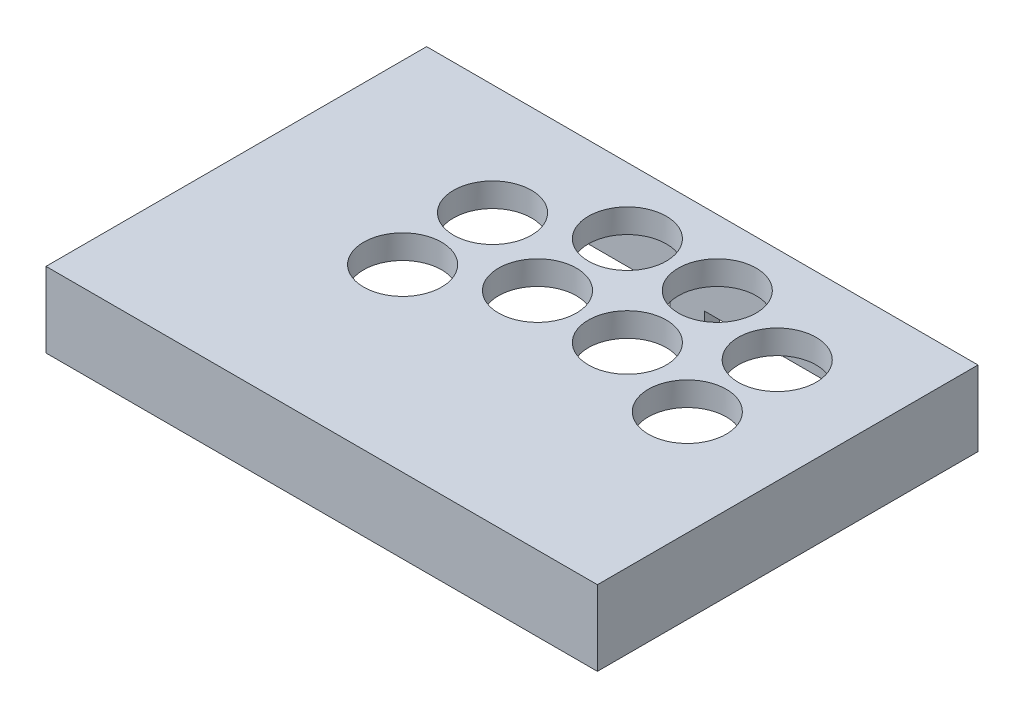
SolidWorks part; units mm, degrees
ref_plane "Front Plane" through (0, 0, 0) normal (0, 0, 1) x (1, 0, 0)
ref_plane "Top Plane" through (0, 0, 0) normal (0, 1, 0) x (1, 0, 0)
ref_plane "Right Plane" through (0, 0, 0) normal (1, 0, 0) x (0, 0, -1)
sketch "Sketch1" plane through (0, 0, 0) normal (0, 1, 0) x (1, 0, 0)
  line L0 (-58.3649, 63.5) -> (-58.3649, -63.5) construction
  line L5 (127, 63.5) -> (-127, 63.5)
  line L6 (127, 63.5) -> (127, -63.5)
  line L7 (127, -63.5) -> (-127, -63.5)
  line L8 (-127, 63.5) -> (-127, -63.5)
  point P0 (0, 0)
  dimension "D1" = 254
  dimension "D2" = 68.6351
  dimension "1" = 127
extrude "Boss-Extrude2" add sketch "Sketch1" along normal blind 19.05
sketch "Sketch2" plane through (0, 0, 0) normal (0, -1, 0) x (1, 0, 0)
  line L12 (-122, 58.5) -> (-122, -58.5)
  line L13 (-122, -58.5) -> (122, -58.5)
  line L14 (122, -58.5) -> (122, 58.5)
  line L15 (122, 58.5) -> (-122, 58.5)
  line L16 (-122, 58.5) -> (-122, -58.5)
  line L17 (-122, -58.5) -> (122, -58.5)
  line L18 (122, -58.5) -> (122, 58.5)
  line L19 (122, 58.5) -> (-122, 58.5)
  dimension "D1" = 5
extrude "Cut-Extrude1" cut sketch "Sketch2" against normal blind 17.05 contours L16 L17 L18 L19
sketch "Sketch4" plane through (0, 19.05, 0) normal (0, 1, 0) x (1, 0, 0)
  line L0 (-57, 63.5) -> (-57, -63.5) construction
  line L1 (127, 63.5) -> (-127, 63.5) construction
  line L2 (-127, -63.5) -> (127, -63.5) construction
  line L3 (127, -63.5) -> (127, 63.5) construction
  circle A0 centre (92, 1.5) radius 13
  circle A1 centre (92, 31.5) radius 13
  circle A2 centre (62, 11.5) radius 13
  circle A3 centre (62, 41.5) radius 13
  circle A6 centre (32, 11.5) radius 13
  circle A7 centre (32, 41.5) radius 13
  circle A8 centre (2, -3.5) radius 13
  circle A9 centre (2, 26.5) radius 13
  dimension "D2" = 26
  dimension "D3" = 65
  dimension "D5" = 35
  dimension "D6" = 19
  dimension "D7" = 26
  dimension "D12" = 26
  dimension "D13" = 26
  dimension "D14" = 30
  dimension "D17" = 26
  dimension "D18" = 26
  dimension "D1" = 70
  dimension "D4" = 35
  dimension "D8" = 75
  dimension "D9" = 30
  dimension "D10" = 30
  dimension "D11" = 30
  dimension "D15" = 30
  dimension "D16" = 30
  dimension "D19" = 60
  dimension "D20" = 30
  dimension "D21" = 30
  dimension "D22" = 30
extrude "Cut-Extrude2" cut sketch "Sketch4" against normal blind 17.05 contours A1 | A0 | A7 | A3 | A2 | A6 | A8 | A9
sketch "Sketch5" plane through (0, 0, 0) normal (0, -1, 0) x (1, 0, 0)
  line L0 (-57, 63.5) -> (-57, -63.5) construction
  line L1 (-127, 63.5) -> (127, 63.5) construction
  line L2 (127, -63.5) -> (-127, -63.5) construction
  line L3 (-57, 63.5) -> (-57, -63.5)
  line L4 (-57, -63.5) -> (-127, -63.5)
  line L5 (-127, -63.5) -> (-127, 63.5)
  line L6 (-127, 63.5) -> (-57, 63.5)
  dimension "D1" = 70
extrude "Cut-Extrude3" cut sketch "Sketch5" against normal blind 45
sketch "Sketch6" plane through (0, 17.05, 0) normal (0, -1, 0) x (1, 0, 0)
  line L0 (-57, 58.5) -> (-57, -58.5)
  line L1 (-57, -58.5) -> (-52, -58.5)
  line L2 (-57, -58.5) -> (122, -58.5) construction
  line L3 (-52, -58.5) -> (-52, 58.5)
  line L4 (122, 58.5) -> (-57, 58.5) construction
  line L5 (-52, 58.5) -> (-57, 58.5)
  dimension "D1" = 5
extrude "Boss-Extrude3" add sketch "Sketch6" along normal up to vertex (17.05 mm away)
sketch "Sketch7" plane through (0, 19.05, 0) normal (0, 1, 0) x (1, 0, 0)
  line L4 (127, 63.5) -> (-57, 63.5)
  line L5 (-57, 63.5) -> (-57, -63.5)
  line L6 (-57, -63.5) -> (127, -63.5)
  line L7 (127, -63.5) -> (127, 63.5)
  line L8 (127, 63.5) -> (-57, 63.5)
  line L9 (-57, 63.5) -> (-57, -63.5)
  line L10 (-57, -63.5) -> (127, -63.5)
  line L11 (127, -63.5) -> (127, 63.5)
  circle A1 centre (2, 26.5) radius 13
  circle A2 centre (2, 26.5) radius 13
  circle A3 centre (2, -3.5) radius 13
  circle A4 centre (2, -3.5) radius 13
  circle A5 centre (32, 11.5) radius 13
  circle A6 centre (32, 11.5) radius 13
  circle A7 centre (92, 31.5) radius 13
  circle A8 centre (92, 31.5) radius 13
  circle A9 centre (62, 11.5) radius 13
  circle A10 centre (62, 11.5) radius 13
  circle A11 centre (62, 41.5) radius 13
  circle A12 centre (62, 41.5) radius 13
  circle A13 centre (32, 41.5) radius 13
  circle A14 centre (32, 41.5) radius 13
  circle A15 centre (92, 1.5) radius 13
  circle A16 centre (92, 1.5) radius 13
  dimension "D1" = 0
  dimension "D2" = 0
  dimension "D3" = 0
  dimension "D4" = 0
  dimension "D5" = 0
  dimension "D6" = 0
  dimension "D7" = 0
  dimension "D8" = 0
  dimension "D9" = 0
extrude "Boss-Extrude4" add sketch "Sketch7" along normal blind 6
sketch "Sketch8" plane through (0, 17.05, 0) normal (0, -1, 0) x (1, 0, 0)
  line L0 (118.5, 58.5) -> (122, 58.5)
  line L1 (122, 58.5) -> (122, 55)
  line L4 (122, -55) -> (122, -58.5)
  line L5 (122, -58.5) -> (118.5, -58.5)
  line L6 (-52, -55) -> (-52, -58.5)
  line L7 (-52, -58.5) -> (-48.5, -58.5)
  line L16 (-52, 55) -> (-52, 58.5)
  line L17 (-52, 58.5) -> (-48.5, 58.5)
  arc A8 (118.5, 58.5) -> (122, 55) centre (122, 58.5) ccw
  arc A9 (122, -55) -> (118.5, -58.5) centre (122, -58.5) ccw
  arc A10 (-48.5, -58.5) -> (-52, -55) centre (-52, -58.5) ccw
  arc A11 (-52, 55) -> (-48.5, 58.5) centre (-52, 58.5) ccw
  dimension "D2" = 3.5
  dimension "D1" = 3.5
  dimension "D3" = 3.5
  dimension "D4" = 3.5
extrude "Boss-Extrude5" add sketch "Sketch8" along normal up to surface (17.05 mm away) up to face at (35, 0, 0)
sketch "Sketch9" plane through (0, 0, 0) normal (0, -1, 0) x (1, 0, 0)
  line L3 (29.2686, -58.5) -> (29.2686, -63.5)
  line L4 (29.2686, -58.5) -> (40.7314, -58.5)
  line L5 (40.7314, -63.5) -> (40.7314, -58.5)
  line L6 (40.7314, -63.5) -> (29.2686, -63.5)
  line L7 (127, 63.5) -> (127, -63.5) construction
  line L8 (-57, -63.5) -> (-57, 63.5) construction
  dimension "D1" = 11.4628
  dimension "D2" = 5
  dimension "D3" = 86.2686
  dimension "D4" = 86.2686
extrude "Boss-Extrude6" add sketch "Sketch9" along normal blind 10 contours L6 L3 L4 L5
sketch "Sketch10" plane through (0, 0, 0) normal (0, -1, 0) x (1, 0, 0)
  circle A4 centre (122, -58.5) radius 1.5
  circle A5 centre (122, 58.5) radius 1.5
  circle A6 centre (-52, -58.5) radius 1.5
  circle A7 centre (-52, 58.5) radius 1.5
  dimension "D1" = 3
  dimension "D2" = 3
  dimension "D3" = 3
  dimension "D4" = 3
extrude "Cut-Extrude4" cut sketch "Sketch10" against normal blind 23
sketch "Sketch11" plane through (0, 0, 0) normal (0, -1, 0) x (1, 0, 0)
  line L0 (-52, -33.5) -> (-57, -33.5)
  line L1 (-52, -55) -> (-52, 55) construction
  line L2 (-57, -63.5) -> (-57, 63.5) construction
  line L3 (29.2686, -63.5) -> (-57, -63.5) construction
  line L4 (-57, -33.5) -> (-57, -18.5)
  line L5 (-57, -18.5) -> (-52, -18.5)
  line L6 (-52, -55) -> (-52, 55) construction
  line L7 (-52, -18.5) -> (-52, -33.5)
  dimension "D1" = 30
extrude "Cut-Extrude6" cut sketch "Sketch11" against normal blind 1.5
sketch "Sketch13" plane through (0, 0, -58.5) normal (0, 0, 1) x (1, 0, 0)
  line L0 (-33.3345, 8.089) -> (-27.0345, 8.089)
  line L1 (-43.3345, 8.089) -> (-37.0345, 8.089)
  line L2 (-43.3345, 8.089) -> (-43.3345, 1.789)
  line L3 (-43.3345, 1.789) -> (-37.0345, 1.789)
  line L4 (-37.0345, 8.089) -> (-37.0345, 1.789)
  line L5 (-43.3345, 8.089) -> (-37.0345, 1.789) construction
  line L6 (-43.3345, 1.789) -> (-37.0345, 8.089) construction
  line L7 (-33.3345, 8.089) -> (-33.3345, 1.789)
  line L12 (-33.3345, 1.789) -> (-27.0345, 1.789)
  line L13 (-33.3345, 8.089) -> (-27.0345, 1.789) construction
  line L18 (-33.3345, 1.789) -> (-27.0345, 8.089) construction
  line L19 (-27.0345, 8.089) -> (-27.0345, 1.789)
  line L20 (-23.3345, 8.089) -> (-17.0345, 8.089)
  line L21 (-23.3345, 8.089) -> (-23.3345, 1.789)
  line L22 (-23.3345, 1.789) -> (-17.0345, 1.789)
  line L23 (-23.3345, 8.089) -> (-17.0345, 1.789) construction
  line L24 (-23.3345, 1.789) -> (-17.0345, 8.089) construction
  line L25 (-17.0345, 8.089) -> (-17.0345, 1.789)
  point P0 (-40.1845, 4.939)
  point P7 (-30.1845, 4.939)
  point P12 (-20.1845, 4.939)
  dimension "D1" = 6.3
  dimension "D2" = 6.3
  dimension "D3" = 3
extrude "Cut-Extrude8" cut sketch "Sketch13" against normal blind 4.5
sketch "Sketch15" plane through (0, 17.05, 0) normal (0, -1, 0) x (1, 0, 0)
  line L0 (2, -13.5) -> (2, -39.5) construction
  line L1 (2, -26.5) -> (15, -26.5) construction
  line L2 (2, -26.5) -> (-11, -26.5) construction
  circle A0 centre (2, -26.5) radius 13 construction
sketch "Sketch16" plane through (0, 17.05, 0) normal (0, -1, 0) x (1, 0, 0)
  circle A0 centre (111.1446, 25.0625) radius 1 construction
  circle A1 centre (111.1446, -53.9077) radius 1 construction
  circle A2 centre (-23.9507, -53.9077) radius 1 construction
  circle A3 centre (-23.9507, 25.0625) radius 1 construction
  circle A4 centre (111.1446, 25.0625) radius 1
  circle A5 centre (111.1446, -53.9077) radius 1
  circle A6 centre (-23.9507, -53.9077) radius 1
  circle A7 centre (-23.9507, 25.0625) radius 1
extrude "Cut-Extrude10" cut sketch "Sketch16" against normal blind 5.5
sketch "Sketch17" plane through (0, 0, -63) normal (0, 0, 1) x (1, 0, 0)
  line L0 (-37.0345, 4.939) -> (-43.3345, 4.939) construction
  line L1 (-37.0345, 1.789) -> (-37.0345, 8.089) construction
  line L2 (-43.3345, 8.089) -> (-43.3345, 1.789) construction
  line L3 (-33.3345, 4.939) -> (-27.0345, 4.939) construction
  line L4 (-33.3345, 8.089) -> (-33.3345, 1.789) construction
  line L5 (-27.0345, 1.789) -> (-27.0345, 8.089) construction
  line L6 (-17.0345, 4.939) -> (-23.3345, 4.939) construction
  line L7 (-17.0345, 1.789) -> (-17.0345, 8.089) construction
  line L8 (-23.3345, 8.089) -> (-23.3345, 1.789) construction
  circle A0 centre (-40.1845, 4.939) radius 1.71
  circle A1 centre (-30.1845, 4.939) radius 1.71
  circle A2 centre (-20.1845, 4.939) radius 1.71
  dimension "D1" = 3.42
  dimension "D2" = 3.42
  dimension "D3" = 3.42
extrude "Cut-Extrude11" cut sketch "Sketch17" against normal blind 10
